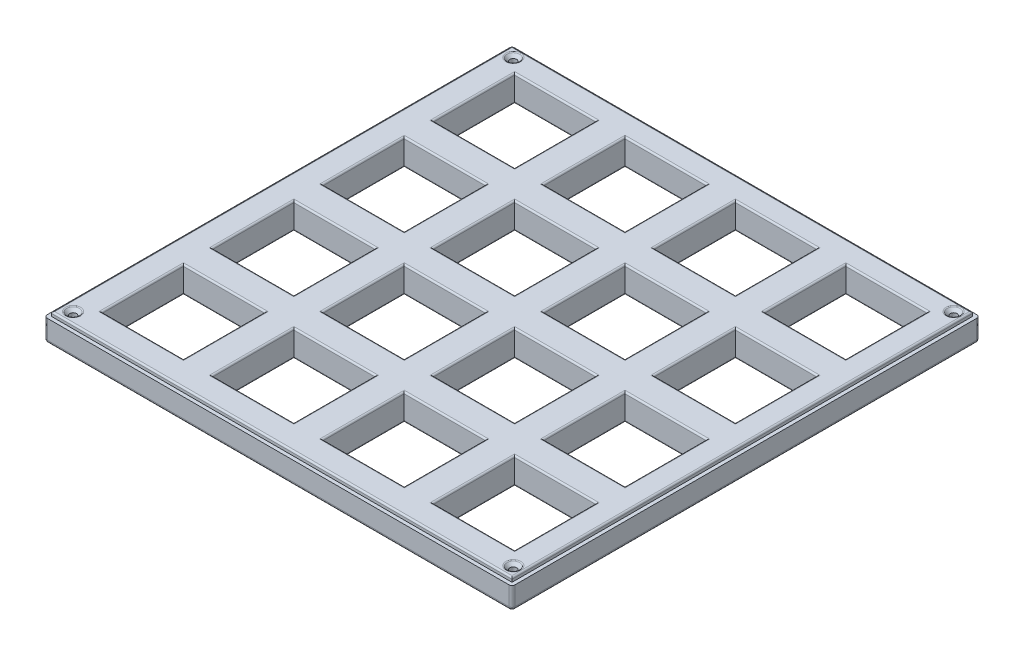
SolidWorks part; units mm, degrees
ref_plane "Front Plane" through (0, 0, 0) normal (0, 0, 1) x (1, 0, 0)
ref_plane "Top Plane" through (0, 0, 0) normal (0, 1, 0) x (1, 0, 0)
ref_plane "Right Plane" through (0, 0, 0) normal (1, 0, 0) x (0, 0, -1)
sketch "Sketch1" plane through (0, 0, 0) normal (0, 1, 0) x (1, 0, 0)
  line L1 (89, -89) -> (-89, -89)
  line L2 (89, -89) -> (89, 89)
  line L3 (89, 89) -> (-89, 89)
  line L4 (-89, -89) -> (-89, 89)
  line L5 (89, -89) -> (-89, 89) construction
  line L6 (89, 89) -> (-89, -89) construction
  point P0 (0, 0)
  dimension "D1" = 178
extrude "Boss-Extrude1" add sketch "Sketch1" along normal blind 10 contours L2 L1 L4 L3
sketch "Sketch2" plane through (0, 10, 0) normal (0, 1, 0) x (1, 0, 0)
  line L0 (89, 89) -> (79, 89) construction
  line L1 (89, 89) -> (-89, 89) construction
  line L2 (79, 89) -> (79, 79) construction
  line L3 (79, 79) -> (89, 79) construction
  line L4 (89, -89) -> (89, 89) construction
  line L5 (89, 79) -> (89, 89) construction
  line L6 (37, 79) -> (37, 48)
  line L7 (79, 79) -> (48, 79)
  line L8 (79, 79) -> (79, 48)
  line L9 (79, 48) -> (48, 48)
  line L10 (48, 79) -> (48, 48)
  line L11 (37, 79) -> (6, 79)
  line L12 (6, 79) -> (6, 48)
  line L13 (37, 48) -> (6, 48)
  line L14 (-5, 79) -> (-5, 48)
  line L15 (-5, 79) -> (-36, 79)
  line L16 (-36, 79) -> (-36, 48)
  line L17 (-5, 48) -> (-36, 48)
  line L18 (-47, 79) -> (-47, 48)
  line L19 (-47, 79) -> (-78, 79)
  line L20 (-78, 79) -> (-78, 48)
  line L21 (-47, 48) -> (-78, 48)
  line L22 (37, 37) -> (37, 6)
  line L23 (37, 37) -> (6, 37)
  line L24 (6, 37) -> (6, 6)
  line L25 (37, 6) -> (6, 6)
  line L26 (-5, 37) -> (-5, 6)
  line L27 (-5, 37) -> (-36, 37)
  line L28 (-36, 37) -> (-36, 6)
  line L29 (-5, 6) -> (-36, 6)
  line L30 (-47, 37) -> (-47, 6)
  line L31 (-47, 37) -> (-78, 37)
  line L32 (-78, 37) -> (-78, 6)
  line L33 (-47, 6) -> (-78, 6)
  line L34 (37, -5) -> (37, -36)
  line L35 (37, -5) -> (6, -5)
  line L36 (6, -5) -> (6, -36)
  line L37 (37, -36) -> (6, -36)
  line L38 (-5, -5) -> (-5, -36)
  line L39 (-5, -5) -> (-36, -5)
  line L40 (-36, -5) -> (-36, -36)
  line L41 (-5, -36) -> (-36, -36)
  line L42 (-47, -5) -> (-47, -36)
  line L43 (-47, -5) -> (-78, -5)
  line L44 (-78, -5) -> (-78, -36)
  line L45 (-47, -36) -> (-78, -36)
  line L46 (37, -47) -> (37, -78)
  line L47 (37, -47) -> (6, -47)
  line L48 (6, -47) -> (6, -78)
  line L49 (37, -78) -> (6, -78)
  line L50 (-5, -47) -> (-5, -78)
  line L51 (-5, -47) -> (-36, -47)
  line L52 (-36, -47) -> (-36, -78)
  line L53 (-5, -78) -> (-36, -78)
  line L54 (-47, -47) -> (-47, -78)
  line L55 (-47, -47) -> (-78, -47)
  line L56 (-78, -47) -> (-78, -78)
  line L57 (-47, -78) -> (-78, -78)
  line L58 (79, 37) -> (79, 6)
  line L59 (79, 37) -> (48, 37)
  line L60 (48, 37) -> (48, 6)
  line L61 (79, 6) -> (48, 6)
  line L62 (79, -5) -> (79, -36)
  line L63 (79, -5) -> (48, -5)
  line L64 (48, -5) -> (48, -36)
  line L65 (79, -36) -> (48, -36)
  line L66 (79, -47) -> (79, -78)
  line L67 (79, -47) -> (48, -47)
  line L68 (48, -47) -> (48, -78)
  line L69 (79, -78) -> (48, -78)
  dimension "D1" = 4
  dimension "D2" = 4
extrude "Cut-Extrude1" cut sketch "Sketch2" against normal blind 10
sketch "Sketch3" plane through (0, 10, 0) normal (0, 1, 0) x (1, 0, 0)
  line L0 (-89, 89) -> (-87.6, 89) construction
  line L1 (-89, 89) -> (89, 89)
  line L2 (-89, 89) -> (-89, -89)
  line L3 (-89, -89) -> (89, -89)
  line L4 (89, 89) -> (89, -89)
  line L5 (-87.6, 89) -> (-87.6, 87.6) construction
  line L6 (-87.6, 87.6) -> (-89, 87.6) construction
  line L7 (-89, 87.6) -> (-89, 89) construction
  line L8 (89, -89) -> (89, -87.6) construction
  line L9 (89, -87.6) -> (87.6, -87.6) construction
  line L10 (87.6, -87.6) -> (87.6, -89) construction
  line L11 (87.6, -89) -> (89, -89) construction
  line L13 (-87.6, 87.6) -> (87.6, 87.6)
  line L14 (-87.6, 87.6) -> (-87.6, -87.6)
  line L15 (-87.6, -87.6) -> (87.6, -87.6)
  line L16 (87.6, 87.6) -> (87.6, -87.6)
extrude "Cut-Extrude2" cut sketch "Sketch3" against normal blind 1.6
sketch "Sketch4" plane through (0, 10, 0) normal (0, 1, 0) x (1, 0, 0)
  line L0 (79, 79) -> (89, 89) construction
  line L1 (-78, 79) -> (-89, 89) construction
  line L2 (89, -89) -> (79, -78) construction
  line L3 (-78, -78) -> (-89, -89) construction
  circle A0 centre (84, 84) radius 1.3
  circle A1 centre (-83.5, 84) radius 1.3
  circle A2 centre (84, -83.5) radius 1.3
  circle A3 centre (-83.5, -83.5) radius 1.3
extrude "Cut-Extrude3" cut sketch "Sketch4" against normal blind 8
chamfer "Chamfer1" distance 1.3 angle 45 4 edges at (84, 10, 84.8) (84, 10, -82.7) (-83.5, 10, -82.7) (-83.5, 10, 84.8)
fillet "Fillet1" radius 0.6 72 edges at (0, 10, -87.6) (87.6, 10, 0) (0, 10, 87.6) (-87.6, 10, 0) (-20.5, 10, 5) (-36, 10, 20.5) (-20.5, 10, 36) (-5, 10, 20.5) (21.5, 10, 5) (6, 10, 20.5) (21.5, 10, 36) (37, 10, 20.5) (-62.5, 10, -37) (-78, 10, -21.5) (-62.5, 10, -6) (-47, 10, -21.5) (-20.5, 10, -37) (-36, 10, -21.5) (-20.5, 10, -6) (-5, 10, -21.5) (21.5, 10, -79) (6, 10, -63.5) (21.5, 10, -48) (37, 10, -63.5) (-20.5, 10, -79) (-36, 10, -63.5) (-20.5, 10, -48) (-5, 10, -63.5) (-62.5, 10, -79) (-78, 10, -63.5) (-62.5, 10, -48) (-47, 10, -63.5) (21.5, 10, -37) (6, 10, -21.5) (21.5, 10, -6) (37, 10, -21.5) (-62.5, 10, 47) (-78, 10, 62.5) (-62.5, 10, 78) (-47, 10, 62.5) (-20.5, 10, 47) (-36, 10, 62.5) (-20.5, 10, 78) (-5, 10, 62.5) (21.5, 10, 47) (6, 10, 62.5) (21.5, 10, 78) (37, 10, 62.5) (-62.5, 10, 5) (-78, 10, 20.5) (-62.5, 10, 36) (-47, 10, 20.5) (63.5, 10, -37) (48, 10, -21.5) (63.5, 10, -6) (79, 10, -21.5) (63.5, 10, 5) (48, 10, 20.5) (63.5, 10, 36) (79, 10, 20.5) (63.5, 10, 47) (48, 10, 62.5) (63.5, 10, 78) (79, 10, 62.5) (79, 10, -63.5) (63.5, 10, -79) (48, 10, -63.5) (63.5, 10, -48) (-83.5, 10, 80.9) (-83.5, 10, -86.6) (84, 10, -86.6) (84, 10, 80.9)
fillet "Fillet2" radius 1.2 8 edges at (-89, 4.2, -89) (-89, 4.2, 89) (89, 4.2, 89) (89, 4.2, -89) (0, 0, -89) (89, 0, 0) (-89, 0, 0) (0, 0, 89)
fillet "Fillet3" radius 0.6 64 edges at (63.5, 0, -79) (79, 0, -63.5) (63.5, 0, -48) (48, 0, -63.5) (48, 0, 62.5) (63.5, 0, 47) (79, 0, 62.5) (63.5, 0, 78) (48, 0, 20.5) (63.5, 0, 5) (79, 0, 20.5) (63.5, 0, 36) (48, 0, -21.5) (63.5, 0, -37) (79, 0, -21.5) (63.5, 0, -6) (-78, 0, 20.5) (-62.5, 0, 5) (-47, 0, 20.5) (-62.5, 0, 36) (6, 0, 62.5) (21.5, 0, 47) (37, 0, 62.5) (21.5, 0, 78) (-36, 0, 62.5) (-20.5, 0, 47) (-5, 0, 62.5) (-20.5, 0, 78) (-78, 0, 62.5) (-62.5, 0, 47) (-47, 0, 62.5) (-62.5, 0, 78) (6, 0, -21.5) (21.5, 0, -37) (37, 0, -21.5) (21.5, 0, -6) (-78, 0, -63.5) (-62.5, 0, -79) (-47, 0, -63.5) (-62.5, 0, -48) (-36, 0, -63.5) (-20.5, 0, -79) (-5, 0, -63.5) (-20.5, 0, -48) (6, 0, -63.5) (21.5, 0, -79) (37, 0, -63.5) (21.5, 0, -48) (-36, 0, -21.5) (-20.5, 0, -37) (-5, 0, -21.5) (-20.5, 0, -6) (-78, 0, -21.5) (-62.5, 0, -37) (-47, 0, -21.5) (-62.5, 0, -6) (6, 0, 20.5) (21.5, 0, 5) (37, 0, 20.5) (21.5, 0, 36) (-36, 0, 20.5) (-20.5, 0, 5) (-5, 0, 20.5) (-20.5, 0, 36)
